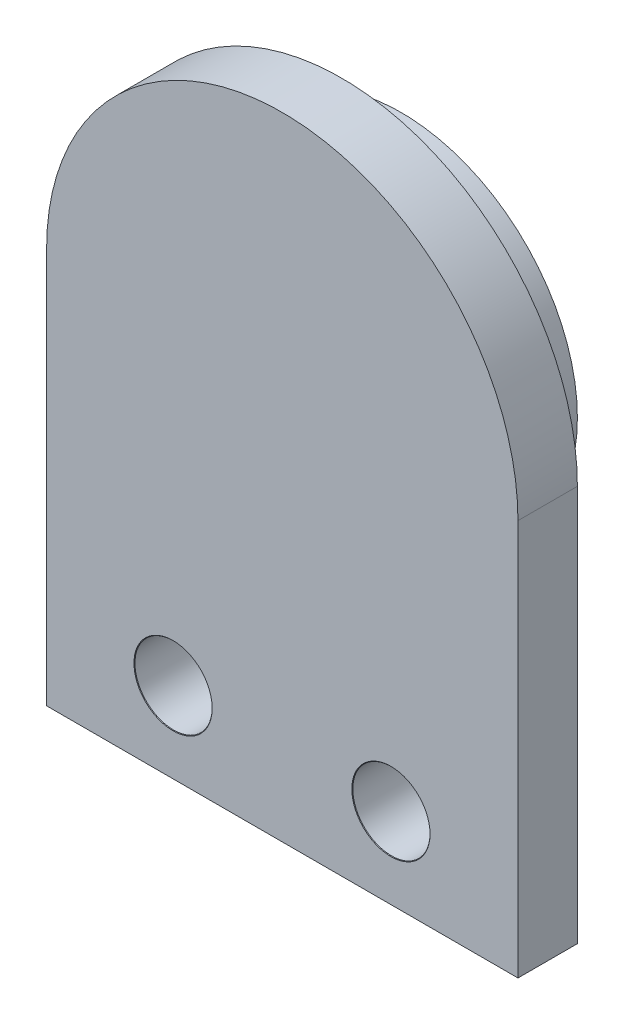
SolidWorks part; units mm, degrees
ref_plane "Front Plane" through (0, 0, 0) normal (0, 0, 1) x (1, 0, 0)
ref_plane "Top Plane" through (0, 0, 0) normal (0, 1, 0) x (1, 0, 0)
ref_plane "Right Plane" through (0, 0, 0) normal (1, 0, 0) x (0, 0, -1)
sketch "Sketch1" plane through (0, 0, 0) normal (0, 0, 1) x (1, 0, 0)
  line L0 (-11.9, 0) -> (-11.9, -20)
  line L1 (-11.9, -20) -> (11.9, -20)
  line L2 (11.9, -20) -> (11.9, 0)
  arc A0 (11.9, 0) -> (-11.9, 0) centre (0, 0) ccw
  dimension "D1" = 20
  dimension "D2" = 23.8
extrude "Boss-Extrude1" add sketch "Sketch1" along normal blind 3
sketch "Sketch2" plane through (0, 0, 0) normal (0, 0, -1) x (-1, 0, 0)
  circle A0 centre (0, 0) radius 8.9
  dimension "D1" = 17.8
extrude "Boss-Extrude2" add sketch "Sketch2" along normal blind 3
sketch "Sketch3" plane through (0, 0, -3) normal (0, 0, -1) x (-1, 0, 0)
  circle A0 centre (0, 0) radius 2
  dimension "D1" = 4
extrude "Boss-Extrude3" add sketch "Sketch3" along normal blind 3
hole_wizard "M3.5 Clearance Hole1" positions "3DSketch1" profile "Sketch5" hole size "M3.5" standard "ANSI Metric"
sketch3d "3DSketch1"
  circle A1 centre (-5.5152, -15.9262, 0) radius 1.975 construction
  circle A3 centre (-5.5152, -15.9262, 0) radius 1.975 construction
  circle A4 centre (5.4848, -15.9262, -0.025) radius 1.95 construction
  circle A5 centre (5.4848, -15.9262, -0.025) radius 1.95 construction
  point P0 (-5.5152, -15.9262, 3)
  point P2 (5.4848, -15.9262, 3)
  point P17 (-5.5152, -15.9262, 1.975)
  point P21 (-5.5152, -15.9262, 1.975)
  point P37 (5.4848, -15.9262, 1.925)
  point P39 (5.4848, -15.9262, 1.925)
  point P45 (5.4848, -15.9262, -0.025)
  point P49 (5.4848, -15.9262, 3)
  point P52 (5.4727, -15.9975, 3)
  point P53 (0, 0, 0)
  point P54 (0, 0, 0)
  point P55 (0, 0, 0)
  point P56 (0, 0, 0)
  point P57 (0, 0, 0)
sketch "Sketch5" plane through (-5.5152, -15.9262, 3) normal (1, 0, 0) x (0, -1, 0)
  line L0 (0, 0) -> (0, 9)
  line L1 (0, 9) -> (1.95, 9)
  line L2 (1.95, 9) -> (1.95, 0.025)
  line L3 (1.95, 0.025) -> (1.975, 0)
  line L5 (1.975, 0) -> (0, 0)
  line L6 (-1.95, 0.025) -> (-1.975, 0) construction
  line L11 (0, -6.35) -> (0, 107.95) construction
  dimension "Thru Hole Dia." = 3.9
  dimension "Thru Hole Depth" = 9
  dimension "Near C'Sink Dia." = 3.95
  dimension "Near C'Sink Angle" = 90
